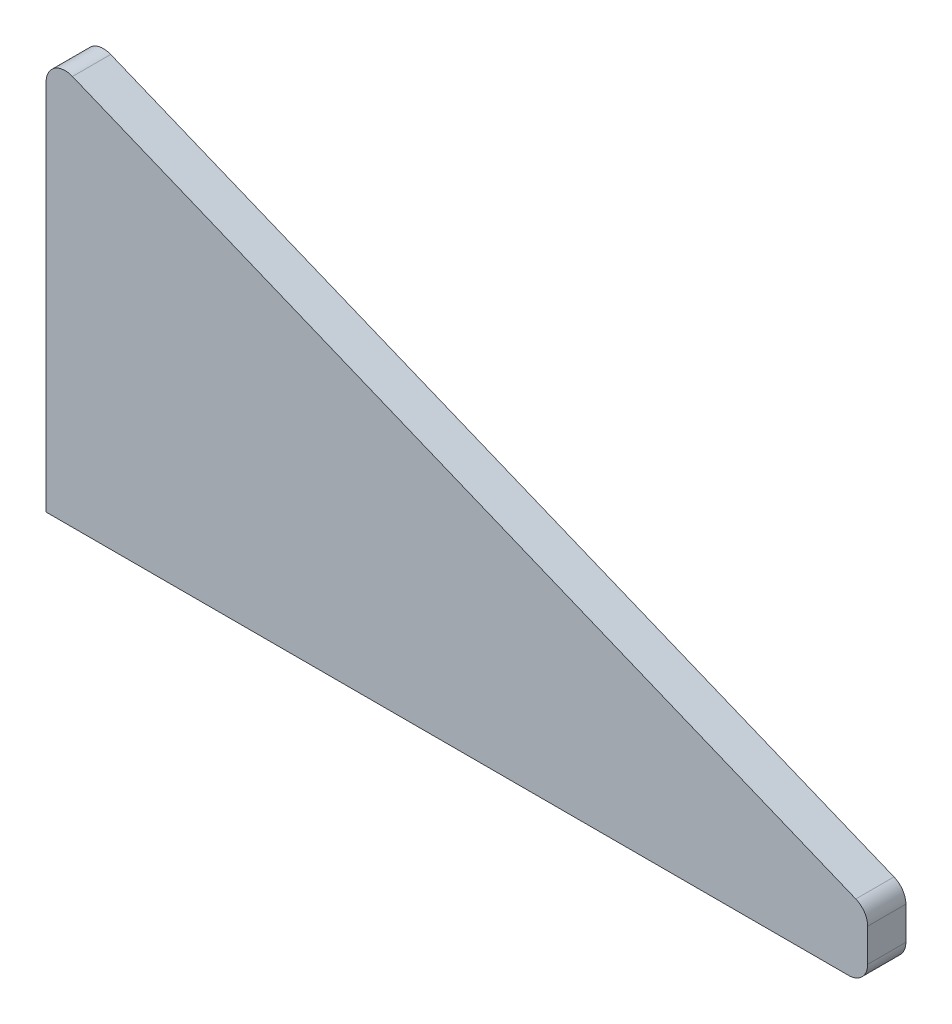
SolidWorks part; units mm, degrees
ref_plane "Front Plane" through (0, 0, 0) normal (0, 0, 1) x (1, 0, 0)
ref_plane "Top Plane" through (0, 0, 0) normal (0, 1, 0) x (1, 0, 0)
ref_plane "Right Plane" through (0, 0, 0) normal (1, 0, 0) x (0, 0, -1)
sketch "Sketch1" plane through (0, 0, 0) normal (0, 0, 1) x (1, 0, 0)
  line L0 (-78.611, 52.3849) -> (126.389, -31.5221)
  line L2 (-85.505, 47.7575) -> (-85.505, -49.7933)
  line L3 (-85.505, -49.7933) -> (124.495, -49.7933)
  line L4 (129.495, -36.1494) -> (129.495, -44.7933)
  arc A0 (126.389, -31.5221) -> (129.495, -36.1494) centre (124.495, -36.1494) cw
  arc A1 (129.495, -44.7933) -> (124.495, -49.7933) centre (124.495, -44.7933) cw
  arc A2 (-85.505, 47.7575) -> (-78.611, 52.3849) centre (-80.505, 47.7575) cw
  point P6 (129.495, -32.7933)
  point P9 (129.495, -49.7933)
  point P12 (-85.505, 55.2067)
  dimension "D4" = 5
  dimension "D1" = 215
  dimension "D2" = 105
  dimension "D3" = 17
extrude "Boss-Extrude1" add sketch "Sketch1" along normal blind 10
